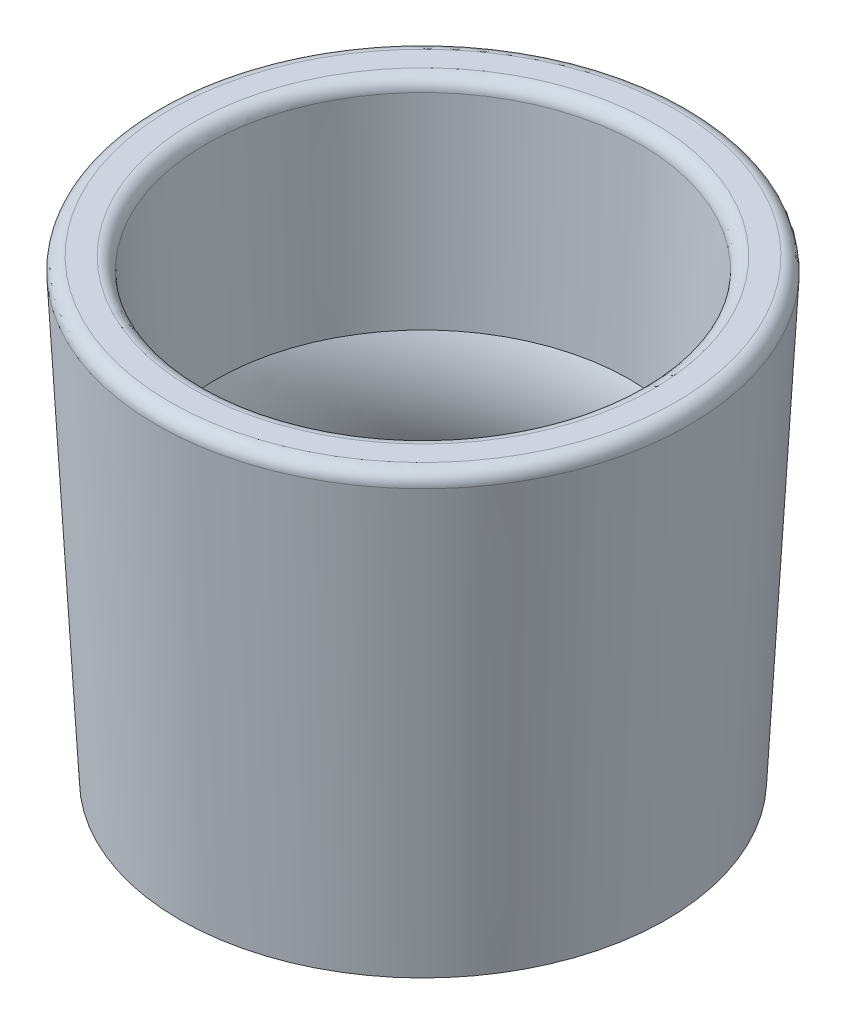
SolidWorks part; units mm, degrees
ref_plane "Ebene vorne" through (0, 0, 0) normal (0, 0, 1) x (1, 0, 0)
ref_plane "Ebene oben" through (0, 0, 0) normal (0, 1, 0) x (1, 0, 0)
ref_plane "Ebene rechts" through (0, 0, 0) normal (1, 0, 0) x (0, 0, -1)
sketch "Skizze1" plane through (0, 0, 0) normal (0, 1, 0) x (1, 0, 0)
  circle A0 centre (0, 0) radius 7.5
  dimension "D1" = 15
extrude "Aufsatz-Linear austragen1" add sketch "Skizze1" along normal blind 14 draft 3 draft outward yes
sketch "Skizze2" plane through (0, 0, 0) normal (0, 0, 1) x (1, 0, 0)
  line L0 (-6.2338, 4.5) -> (-6.0766, 1.5)
  line L2 (-6.7358, 14.0785) -> (-6.0021, 0.0785)
  line L3 (-6.7317, 14) -> (-6.391, 7.5)
  line L4 (0, 0) -> (0, 1.5) construction
  line L5 (-7.5, 1.5) -> (7.5, 1.5)
  line L6 (-6.0766, 1.5) -> (0, 1.5)
  line L7 (-6.7317, 14) -> (0, 14)
  line L8 (8.2337, 14) -> (-8.2337, 14) construction
  line L9 (0, 1.5) -> (0, 14)
  arc A0 (-6.391, 7.5) -> (-6.2338, 4.5) centre (-10.0146, 5.806) cw
  point P17 (0, 13.8615)
  dimension "D3" = 4
  dimension "D4" = 3
  dimension "D5" = 3
  dimension "D1" = 1.5
  dimension "D2" = 1.5
revolve "Schnitt-Rotation1" cut sketch "Skizze2" angle 360 about L4
sketch "Skizze3" plane through (0, 1.5, 0) normal (0, 1, 0) x (1, 0, 0)
  circle A0 centre (0, 0) radius 0.8
  dimension "D1" = 1.6
extrude "Schnitt-Linear austragen1" cut sketch "Skizze3" against normal through all
fillet "Verrundung1" radius 0.4 2 edges at (0, 14, 8.2337) (0, 14, -6.7317)
